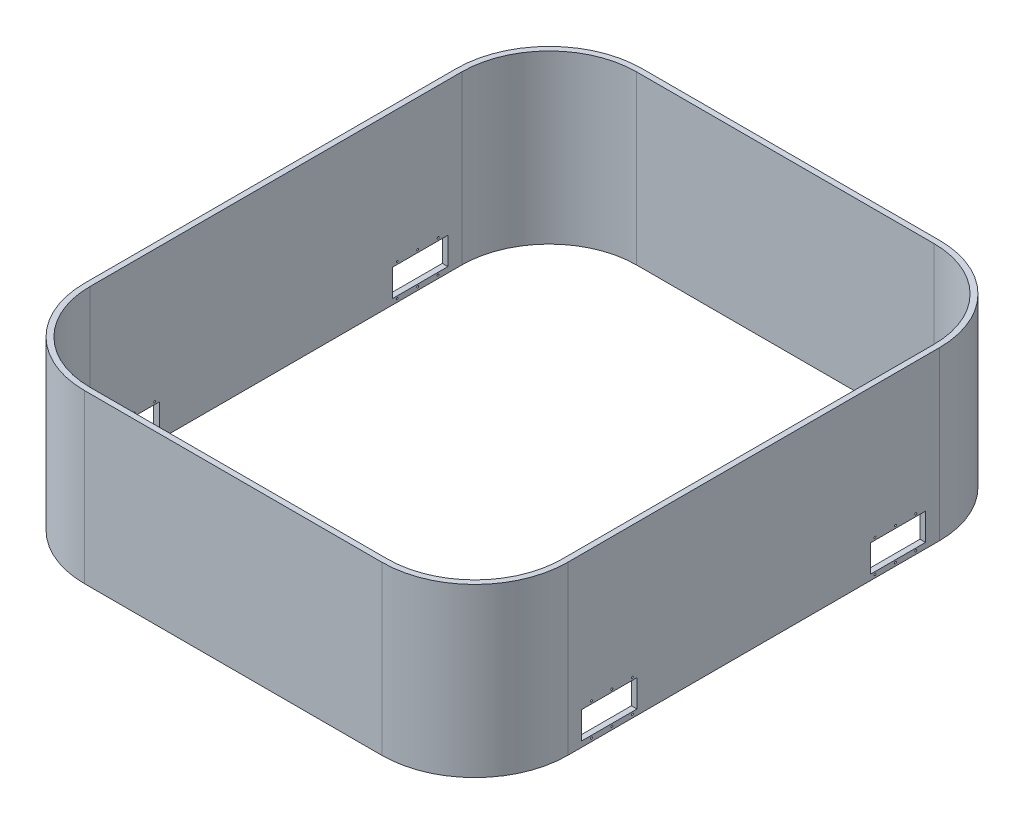
SolidWorks part; units mm, degrees
material "6063-O"
ref_plane "Plano frontal" through (0, 0, 0) normal (0, 0, 1) x (1, 0, 0)
ref_plane "Plano superior" through (0, 0, 0) normal (0, 1, 0) x (1, 0, 0)
ref_plane "Plano direito" through (0, 0, 0) normal (1, 0, 0) x (0, 0, -1)
sketch "Chapa inferior" plane through (0, 0, 0) normal (0, 1, 0) x (1, 0, 0)
  line L1 (-160, 300) -> (160, 300)
  line L2 (-260, 200) -> (-260, -200)
  line L3 (-160, -300) -> (160, -300)
  line L4 (260, 200) -> (260, -200)
  line L5 (-260, 300) -> (260, -300) construction
  line L6 (-260, -300) -> (260, 300) construction
  arc A0 (160, 300) -> (260, 200) centre (160, 200) cw
  arc A1 (160, -300) -> (260, -200) centre (160, -200) ccw
  arc A2 (-260, -200) -> (-160, -300) centre (-160, -200) ccw
  arc A3 (-160, 300) -> (-260, 200) centre (-160, 200) ccw
  point P0 (0, 0)
  dimension "D3" = 100
  dimension "D4" = 100
  dimension "D5" = 100
  dimension "D6" = 100
  dimension "D1" = 520
  dimension "D2" = 600
extrude "ChapaLateral" add sketch "Chapa inferior" along normal blind 180 thin
sketch "Esboço8" plane through (254, 0, 0) normal (-1, 0, 0) x (0, 0, 1)
  line L0 (-200, 180) -> (-200, 0) construction
  line L1 (-185, 6) -> (-125.5, 6)
  line L2 (-185, 6) -> (-185, 35.2)
  line L3 (-185, 35.2) -> (-125.5, 35.2)
  line L4 (-125.5, 6) -> (-125.5, 35.2)
  line L5 (-185, 6) -> (-125.5, 35.2) construction
  line L6 (-185, 35.2) -> (-125.5, 6) construction
  line L7 (200, 0) -> (-200, 0) construction
  point P0 (-155.25, 20.6)
  dimension "D1" = 59.5
  dimension "D2" = 15
  dimension "D3" = 29.2
  dimension "D4" = 6
sketch "Esboço10" plane through (254, 0, 0) normal (-1, 0, 0) x (0, 0, 1)
  line L1 (125.5, 6) -> (185, 6)
  line L2 (125.5, 6) -> (125.5, 35.2)
  line L3 (125.5, 35.2) -> (185, 35.2)
  line L4 (185, 6) -> (185, 35.2)
  line L5 (125.5, 6) -> (185, 35.2) construction
  line L6 (125.5, 35.2) -> (185, 6) construction
  line L8 (200, 180) -> (200, 0) construction
  line L9 (200, 0) -> (-200, 0) construction
  point P0 (155.25, 20.6)
  dimension "D1" = 59.5
  dimension "D2" = 15
  dimension "D3" = 29.2
  dimension "D4" = 6
extrude "MotorTraseiro" cut sketch "Esboço8" against normal through all both and the other way through all
extrude "MotorFrontal" cut sketch "Esboço10" against normal through all both and the other way through all
sketch "Esboço15" plane through (-260, 0, 0) normal (-1, 0, 0) x (0, 0, 1)
  line L1 (185, 6) -> (185, 35.2) construction
  line L2 (185, 35.2) -> (125.5, 35.2) construction
  line L3 (125.5, 35.2) -> (125.5, 6) construction
  line L7 (0, 0) -> (0, 180) construction
  line L8 (-200, 0) -> (200, 0) construction
  line L9 (-200, 180) -> (200, 180) construction
  circle A0 centre (174.5, 38) radius 1.025
  circle A1 centre (152.5, 38) radius 1.025
  circle A2 centre (130.5, 38) radius 1.025
  circle A3 centre (152.5, 3.4) radius 1.025
  circle A4 centre (130.5, 3.4) radius 1.025
  circle A5 centre (174.5, 3.4) radius 1.025
  circle A12 centre (-174.5, 3.4) radius 1.025
  circle A13 centre (-130.5, 3.4) radius 1.025
  circle A14 centre (-152.5, 3.4) radius 1.025
  circle A15 centre (-130.5, 38) radius 1.025
  circle A16 centre (-152.5, 38) radius 1.025
  circle A17 centre (-174.5, 38) radius 1.025
  dimension "D1" = 10.5
  dimension "D2" = 2.8
  dimension "D3" = 3
  dimension "D5" = 5
  dimension "D4" = 2
extrude "FurosDynamixel" cut sketch "Esboço15" against normal through all both and the other way through all
